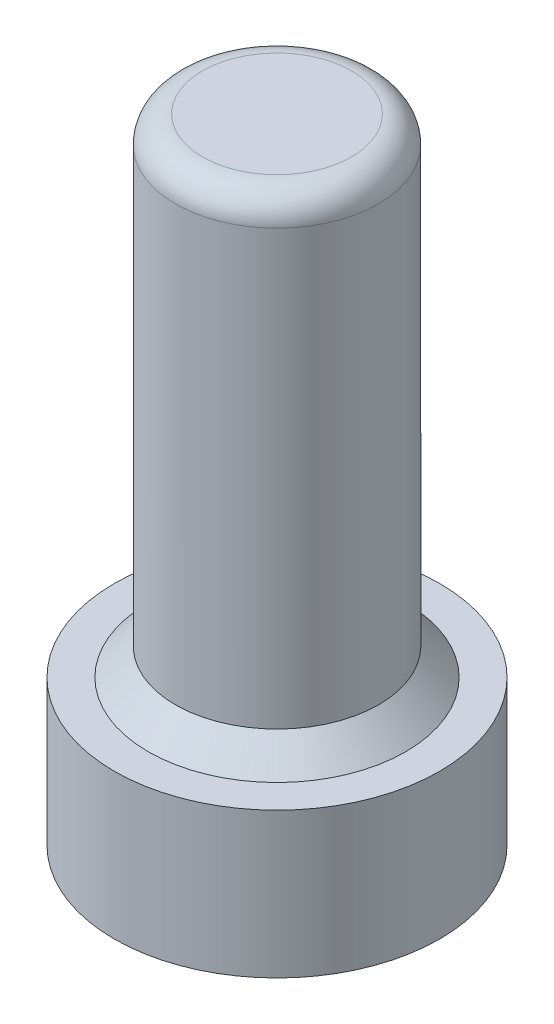
SolidWorks part; units mm, degrees
ref_plane "Front Plane" through (0, 0, 0) normal (0, 0, 1) x (1, 0, 0)
ref_plane "Top Plane" through (0, 0, 0) normal (0, 1, 0) x (1, 0, 0)
ref_plane "Right Plane" through (0, 0, 0) normal (1, 0, 0) x (0, 0, -1)
sketch "Sketch1" plane through (0, 0, 0) normal (0, 0, 1) x (1, 0, 0)
  line L0 (0, -1000) -> (0, 49000) construction
  line L1 (0, 11.68) -> (1.875, 11.68)
  line L2 (1.875, 11.68) -> (1.875, 3.18)
  line L3 (1.875, 3.18) -> (2.375, 2.68)
  line L4 (2.375, 2.68) -> (3, 2.68)
  line L5 (3, 2.68) -> (3, 0)
  line L6 (3, 0) -> (0, 0)
  line L7 (0, 0) -> (0, 11.68)
  dimension "D1" = 3.75
  dimension "D2" = 11.68
  dimension "D3" = 6
  dimension "D4" = 2.68
  dimension "D5" = 45
  dimension "D6" = 0.5
revolve "Revolve1" add sketch "Sketch1" angle 360 about L0
fillet "Fillet1" radius 0.5 1 edges at (1.875, 11.68, 0)
